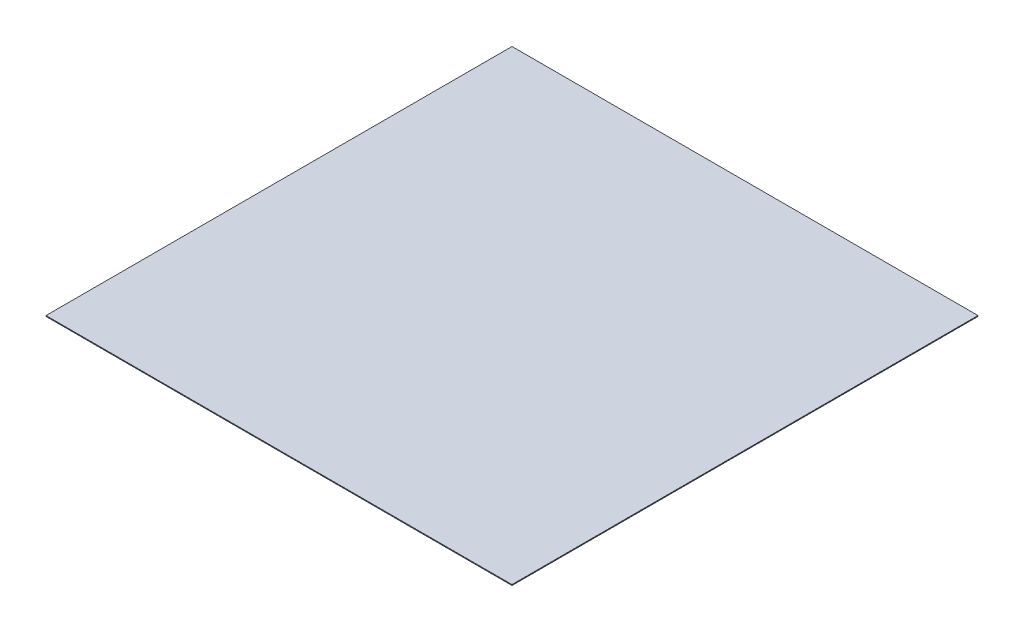
SolidWorks part; units mm, degrees
ref_plane "Front Plane" through (0, 0, 0) normal (0, 0, 1) x (1, 0, 0)
ref_plane "Top Plane" through (0, 0, 0) normal (0, 1, 0) x (1, 0, 0)
ref_plane "Right Plane" through (0, 0, 0) normal (1, 0, 0) x (0, 0, -1)
sketch "Sketch1" plane through (0, 0, 0) normal (0, 1, 0) x (1, 0, 0)
  line L1 (-282.8427, -282.8427) -> (282.8427, -282.8427)
  line L2 (-282.8427, -282.8427) -> (-282.8427, 282.8427)
  line L3 (-282.8427, 282.8427) -> (282.8427, 282.8427)
  line L4 (282.8427, -282.8427) -> (282.8427, 282.8427)
  line L5 (-282.8427, -282.8427) -> (282.8427, 282.8427) construction
  line L6 (-282.8427, 282.8427) -> (282.8427, -282.8427) construction
  point P0 (0, 0)
  dimension "D1" = 800
  dimension "D2" = 90
extrude "Boss-Extrude1" add sketch "Sketch1" along normal blind 1
